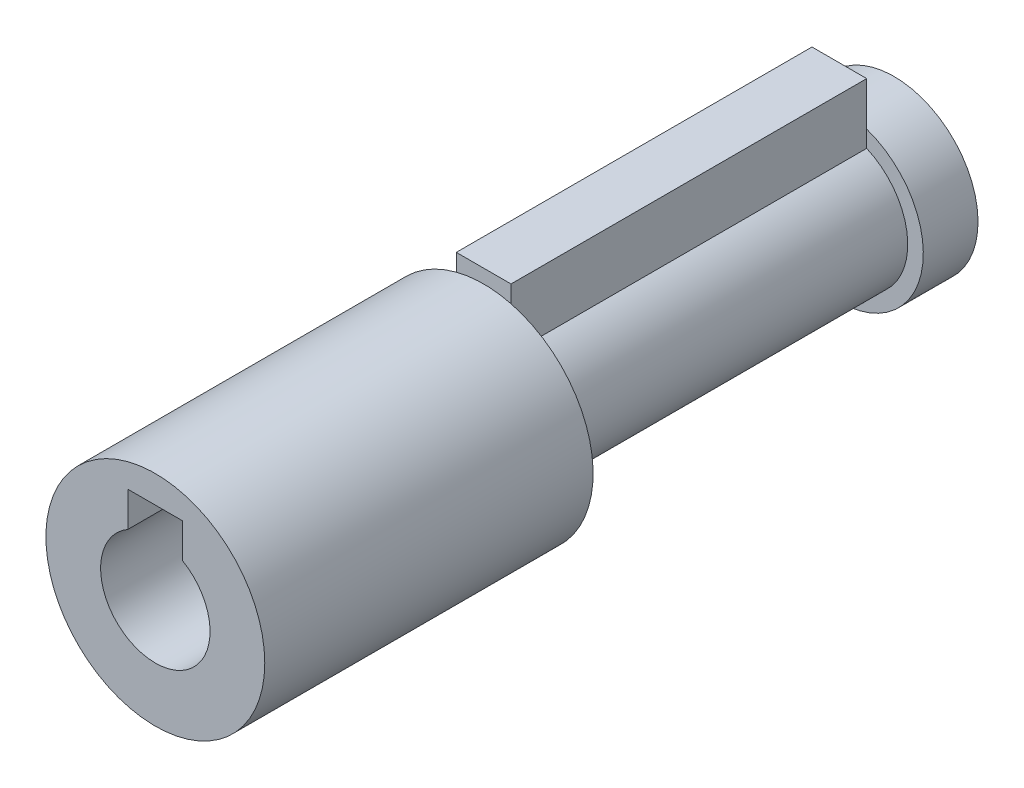
SolidWorks part; units mm, degrees
ref_plane "Front Plane" through (0, 0, 0) normal (0, 0, 1) x (1, 0, 0)
ref_plane "Top Plane" through (0, 0, 0) normal (0, 1, 0) x (1, 0, 0)
ref_plane "Right Plane" through (0, 0, 0) normal (1, 0, 0) x (0, 0, -1)
sketch "Sketch1" plane through (0, 0, 0) normal (0, 0, 1) x (1, 0, 0)
  line L1 (-1.27, 3.81) -> (1.27, 3.81)
  line L2 (-1.27, 3.81) -> (-1.27, 2.1997)
  line L4 (1.27, 3.81) -> (1.27, 2.1997)
  line L5 (-1.27, 3.81) -> (0, 2.54) construction
  line L6 (0, 2.54) -> (1.27, 3.81) construction
  circle A0 centre (0, 0) radius 2.54
  circle A1 centre (0, 0) radius 5.08
  point P4 (0, 2.54)
extrude "Boss-Extrude1" add sketch "Sketch1" along normal blind 12.7 contours A1 A0 L2 L1 L4
sketch "Sketch3" plane through (0, 0, 0) normal (0, 0, -1) x (-1, 0, 0)
  circle A0 centre (0, 0) radius 5.08
extrude "Boss-Extrude5" add sketch "Sketch3" along normal blind 2.54
sketch "Sketch5" plane through (0, 0, -2.54) normal (0, 0, -1) x (-1, 0, 0)
  line L1 (-1.27, 5.715) -> (1.27, 5.715)
  line L2 (-1.27, 5.715) -> (-1.27, 2.9099)
  line L4 (1.27, 5.715) -> (1.27, 2.9099)
  line L5 (-1.27, 5.715) -> (0, 3.175) construction
  line L6 (0, 3.175) -> (1.27, 5.715) construction
  arc A0 (-1.27, 2.9099) -> (1.27, 2.9099) centre (0, 0) ccw
  point P3 (0, 3.175)
extrude "Boss-Extrude7" add sketch "Sketch5" along normal blind 16.51
sketch "Sketch6" plane through (0, 0, -19.05) normal (0, 0, -1) x (-1, 0, 0)
  circle A0 centre (0, 0) radius 3.8971
extrude "Boss-Extrude8" add sketch "Sketch6" along normal blind 2.54
